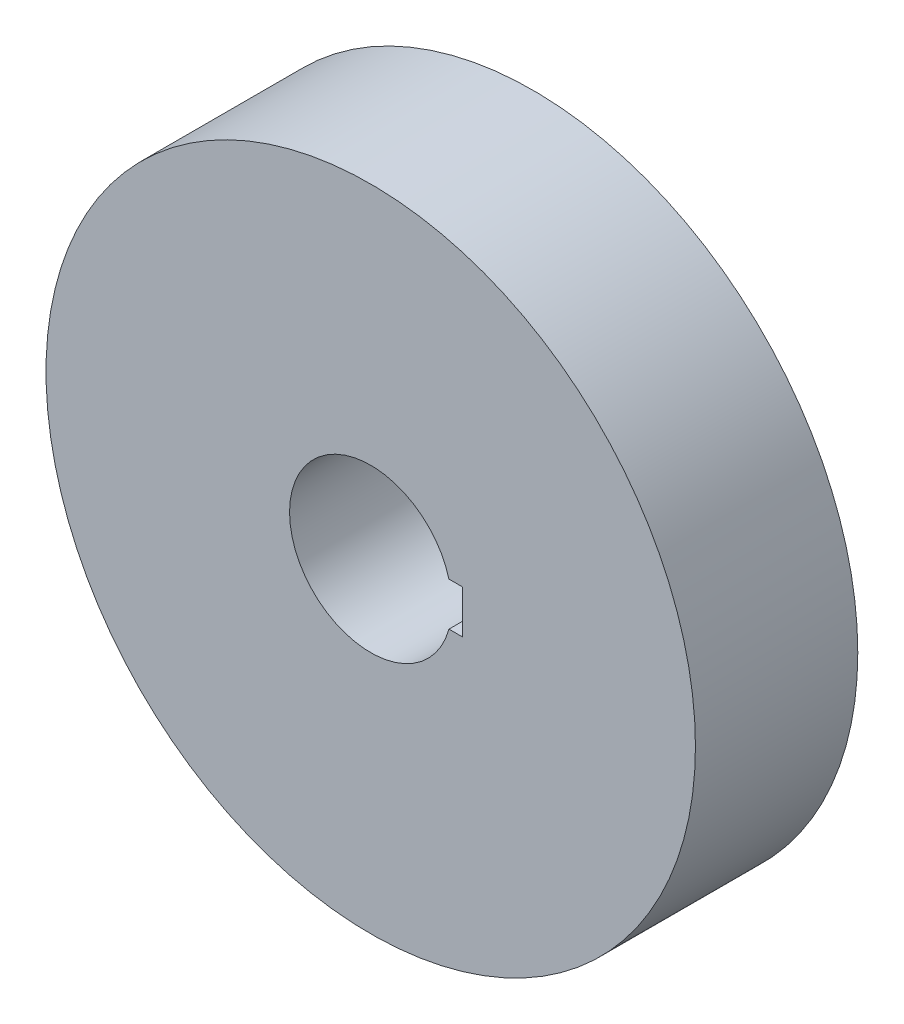
SolidWorks part; units mm, degrees
ref_plane "前视基准面" through (0, 0, 0) normal (0, 0, 1) x (1, 0, 0)
ref_plane "上视基准面" through (0, 0, 0) normal (0, 1, 0) x (1, 0, 0)
ref_plane "右视基准面" through (0, 0, 0) normal (1, 0, 0) x (0, 0, -1)
sketch "草图1" plane through (0, 0, 0) normal (0, 0, 1) x (1, 0, 0)
  circle A0 centre (0, 0) radius 30
  dimension "D1" = 60
extrude "凸台-拉伸1" add sketch "草图1" along normal mid plane 15
sketch "草图2" plane through (0, 0, 7.5) normal (0, 0, 1) x (1, 0, 0)
  line L1 (7.2284, 2) -> (8.5, 2)
  line L3 (7.2284, -2) -> (8.5, -2)
  line L4 (8.5, 2) -> (8.5, -2)
  line L6 (6.5, 0) -> (7.5, 0) construction
  arc A0 (7.2284, 2) -> (7.2284, -2) centre (0, 0) ccw
  point P3 (7.5, 0)
  dimension "D1" = 15
  dimension "D2" = 8.5
extrude "切除-拉伸1" cut sketch "草图2" against normal blind 30
